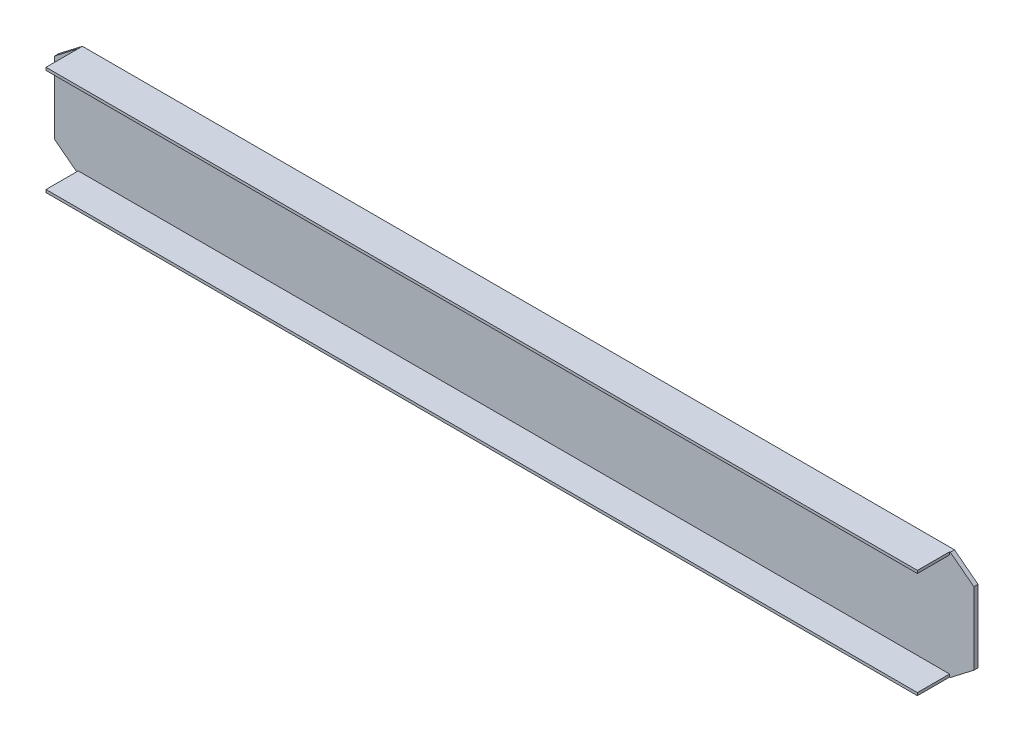
SolidWorks part; units mm, degrees
ref_plane "前视" through (0, 0, 0) normal (0, 0, 1) x (1, 0, 0)
ref_plane "上视" through (0, 0, 0) normal (0, 1, 0) x (1, 0, 0)
ref_plane "右视" through (0, 0, 0) normal (1, 0, 0) x (0, 0, -1)
sketch "草图1" plane through (0, 0, 0) normal (0, 0, 1) x (1, 0, 0)
  line L0 (0, -30.9807) -> (0, 402.9291) construction
  line L1 (-1205, 0) -> (1205, 0)
  line L2 (-1270, 50) -> (-1270, 250)
  line L3 (-1205, 300) -> (1205, 300)
  line L4 (-1270, 50) -> (-1205, 0)
  line L5 (-1270, 250) -> (-1205, 300)
  line L6 (-1329.5124, 150) -> (23.7415, 150) construction
  line L7 (-1307.9834, 230) -> (-31.6189, 230) construction
  line L8 (-1220, -101.4655) -> (-1220, 369.0978) construction
  line L9 (1270, 250) -> (1205, 300)
  line L10 (-1140, 369.0978) -> (-1140, -101.4655) construction
  line L11 (1270, 50) -> (1205, 0)
  line L12 (-1060, -101.4655) -> (-1060, 369.0978) construction
  line L13 (1270, 50) -> (1270, 250)
  line L14 (-980, 369.0978) -> (-980, -101.4655) construction
  point P8 (0, 300)
  point P65 (0, 0)
  dimension "D1" = 1205
  dimension "D2" = 300
  dimension "D3" = 65
  dimension "D4" = 65
  dimension "D5" = 50
  dimension "D6" = 50
  dimension "D7" = 70
  dimension "D8" = 80
  dimension "D9" = 50
  dimension "D10" = 80
  dimension "D11" = 80
  dimension "D12" = 80
extrude "基体-拉伸" add sketch "草图1" against normal blind 11.5
sketch "草图2" plane through (0, 0, 0) normal (0, 0, 1) x (1, 0, 0)
  line L0 (-1399.9508, 150) -> (-832.4876, 150) construction
  line L1 (-1205, 300) -> (1203.049, 300)
  line L2 (-1205, 300) -> (-1205, 292.5)
  line L3 (-1205, 292.5) -> (1203.049, 292.5)
  line L4 (1203.049, 300) -> (1203.049, 292.5)
  line L5 (-1205, 0) -> (1205, 0) construction
  line L6 (1203.049, 0) -> (1203.049, 7.5)
  line L7 (-1205, 7.5) -> (1203.049, 7.5)
  line L8 (-1205, 0) -> (-1205, 7.5)
  line L9 (-1205, 0) -> (1203.049, 0)
  dimension "D1" = 7.5
extrude "凸台-拉伸1" add sketch "草图2" along normal blind 89
sketch "草图3" plane through (0, 0, -11.5) normal (0, 0, -1) x (-1, 0, 0)
  line L0 (0, -46.5184) -> (0, 412.0245) construction
  line L1 (-180, 412.0245) -> (-180, -46.5184) construction
  line L2 (-580, 412.0245) -> (-580, -73.5011) construction
  line L3 (-1205, 300) -> (1205, 300) construction
  line L4 (-620, 270) -> (-540, 270)
  line L5 (-620, 270) -> (-620, 30)
  line L6 (-620, 30) -> (-540, 30)
  line L7 (-540, 270) -> (-540, 30)
  line L8 (-220, 270) -> (-140, 270)
  line L9 (-220, 270) -> (-220, 30)
  line L10 (-220, 30) -> (-140, 30)
  line L11 (-140, 270) -> (-140, 30)
  line L12 (140, 270) -> (140, 30)
  line L13 (220, 30) -> (140, 30)
  line L14 (220, 270) -> (220, 30)
  line L15 (220, 270) -> (140, 270)
  line L16 (540, 270) -> (540, 30)
  line L17 (620, 30) -> (540, 30)
  line L18 (620, 270) -> (620, 30)
  line L19 (620, 270) -> (540, 270)
  dimension "D1" = 180
  dimension "D2" = 400
  dimension "D3" = 240
  dimension "D4" = 30
  dimension "D5" = 80
  dimension "D6" = 80
extrude "凸台-拉伸2" add sketch "草图3" along normal blind 16
